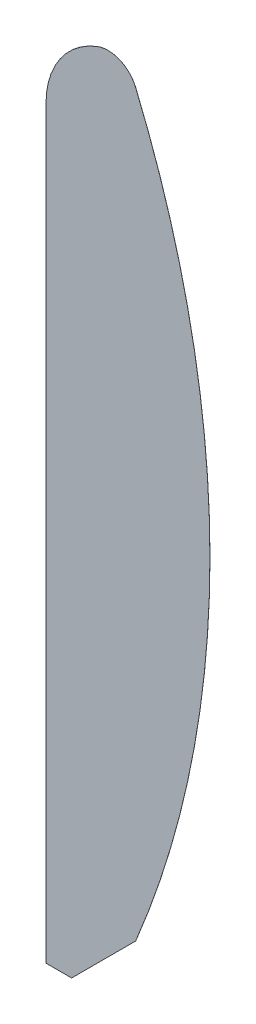
SolidWorks part; units mm, degrees
ref_plane "Front Plane" through (0, 0, 0) normal (1, 0, 0) x (0, 1, 0)
ref_plane "Top Plane" through (0, 0, 0) normal (0, 0, 1) x (0, 1, 0)
ref_plane "Right Plane" through (0, 0, 0) normal (0, 1, 0) x (-1, 0, 0)
sketch "Sketch1" plane through (0, 0, 0) normal (0, 0, 1) x (0, 1, 0)
  line L0 (0, 0) -> (0, 46433.2994) construction
  line L1 (0, 0) -> (-46433.2994, 0) construction
  line L2 (341.0561, 447.2498) -> (1519.4065, 281.6435) construction
  line L3 (0, 0) -> (145.44, 0)
  line L9 (0, 0) -> (0, -5)
  line L10 (0, -5) -> (12.5, -17.5)
  line L11 (0, 0) -> (84.6491, -32)
  arc A0 (145.44, 0) -> (160, -10) centre (145.44, -15.5997) cw
  arc A1 (160, -10) -> (156.7982, -17.5) centre (154.5368, -12.1011) cw
  arc A2 (12.5, -17.5) -> (156.7982, -17.5) centre (84.6491, 154.7496) ccw
  dimension "D1" = 145.44
  dimension "D2" = 5
  dimension "D3" = 32
  dimension "D4" = 17.5
  dimension "Span" = 160
  dimension "D6" = 12.5
  dimension "D7" = 10
extrude "Boss-Extrude1" add sketch "Sketch1" along normal blind 0.01 contours L3 A0 A1 A2 L10 L9
equation "\"D3@Sketch1\"=\"Span@Sketch1\"/5"
equation "\"D1@Sketch1\"=\"Span@Sketch1\"*0.909"
